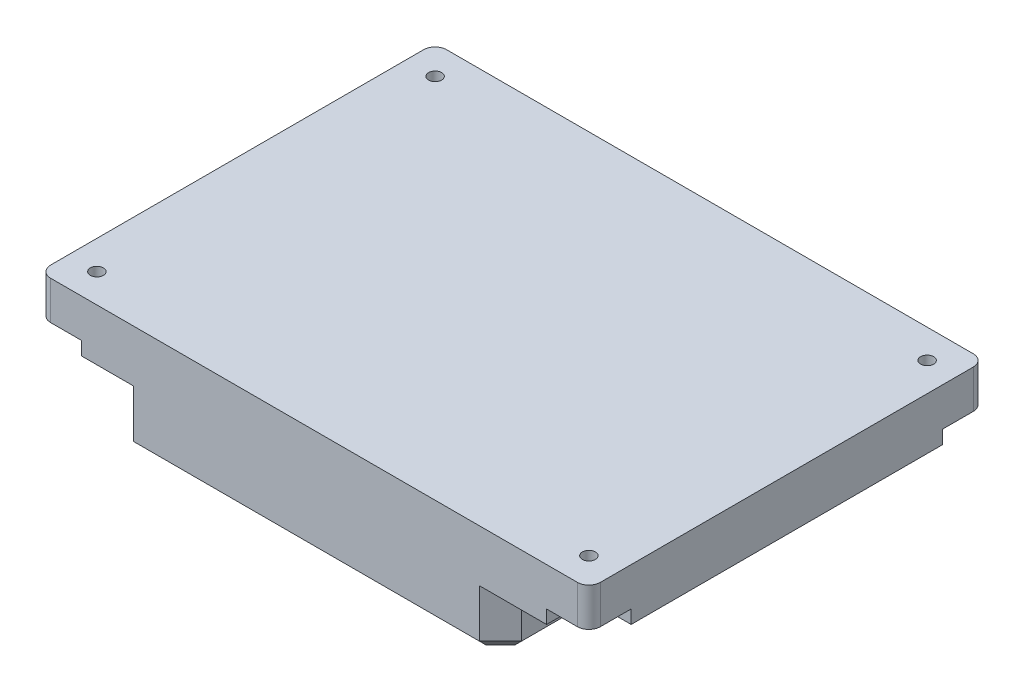
SolidWorks part; units mm, degrees
ref_plane "Front Plane" through (0, 0, 0) normal (0, 0, 1) x (1, 0, 0)
ref_plane "Top Plane" through (0, 0, 0) normal (0, 1, 0) x (1, 0, 0)
ref_plane "Right Plane" through (0, 0, 0) normal (1, 0, 0) x (0, 0, -1)
ref_plane "Plane1" through (0, 3, 0) normal (0, 1, 0) x (1, 0, 0)
sketch "Sketch1" plane through (0, 3, 0) normal (0, 1, 0) x (1, 0, 0)
  line L0 (71.5, -48.5) -> (71.5, 48.5)
  line L1 (68.5, 51.5) -> (-68.5, 51.5)
  line L2 (-71.5, 48.5) -> (-71.5, -48.5)
  line L3 (-68.5, -51.5) -> (68.5, -51.5)
  arc A0 (68.5, -51.5) -> (71.5, -48.5) centre (68.5, -48.5) ccw
  arc A1 (71.5, 48.5) -> (68.5, 51.5) centre (68.5, 48.5) ccw
  arc A2 (-68.5, 51.5) -> (-71.5, 48.5) centre (-68.5, 48.5) ccw
  arc A3 (-71.5, -48.5) -> (-68.5, -51.5) centre (-68.5, -48.5) ccw
  circle A22 centre (-64, 44) radius 1.7
  circle A34 centre (-64, -44) radius 1.7
  circle A40 centre (64, -44) radius 1.7
  circle A55 centre (64, 44) radius 1.7
extrude "Boss-Extrude1" add sketch "Sketch1" against normal blind 13.5
sketch "Sketch2" plane through (0, -10.5, 0) normal (0, -1, 0) x (1, 0, 0)
  line L0 (-71.5, -40.5) -> (-63, -40.5)
  line L1 (-71.5, -48.5) -> (-71.5, 48.5) construction
  line L2 (-60.5, -43) -> (-60.5, -51.5)
  line L3 (68.5, -51.5) -> (-68.5, -51.5) construction
  line L4 (-71.5, -40.5) -> (-71.5, -48.5)
  line L5 (-68.5, -51.5) -> (-60.5, -51.5)
  line L6 (-71.5, 40.5) -> (-63, 40.5)
  line L7 (-60.5, 43) -> (-60.5, 51.5)
  line L8 (-68.5, 51.5) -> (68.5, 51.5) construction
  line L9 (-71.5, 48.5) -> (-71.5, 40.5)
  line L10 (60.5, 51.5) -> (60.5, 43)
  line L11 (-68.5, 51.5) -> (-60.5, 51.5)
  line L12 (60.5, -51.5) -> (60.5, -43)
  line L13 (63, -40.5) -> (71.5, -40.5)
  line L14 (71.5, 48.5) -> (71.5, -48.5) construction
  line L15 (71.5, -40.5) -> (71.5, -48.5)
  line L16 (-63, -40.5) -> (-60.5, -43)
  line L17 (63, 40.5) -> (71.5, 40.5)
  line L18 (60.5, -43) -> (63, -40.5)
  line L19 (60.5, 43) -> (63, 40.5)
  line L20 (-63, 40.5) -> (-60.5, 43)
  line L21 (60.5, 51.5) -> (68.5, 51.5)
  line L22 (71.5, 48.5) -> (71.5, 40.5)
  line L23 (60.5, -51.5) -> (68.5, -51.5)
  arc A1 (-71.5, -48.5) -> (-68.5, -51.5) centre (-68.5, -48.5) ccw construction
  arc A3 (-68.5, 51.5) -> (-71.5, 48.5) centre (-68.5, 48.5) ccw construction
  arc A8 (71.5, 48.5) -> (68.5, 51.5) centre (68.5, 48.5) ccw construction
  arc A9 (-68.5, 51.5) -> (-71.5, 48.5) centre (-68.5, 48.5) ccw
  arc A10 (68.5, -51.5) -> (71.5, -48.5) centre (68.5, -48.5) ccw construction
  arc A11 (71.5, 48.5) -> (68.5, 51.5) centre (68.5, 48.5) ccw
  arc A12 (-71.5, -48.5) -> (-68.5, -51.5) centre (-68.5, -48.5) ccw
  arc A13 (68.5, -51.5) -> (71.5, -48.5) centre (68.5, -48.5) ccw
  point P1 (-60.5, -40.5)
  point P8 (-60.5, 40.5)
  point P15 (60.5, -40.5)
  point P24 (60.5, 40.5)
  dimension "D1" = 11
  dimension "D2" = 11
extrude "Cut-Extrude2" cut sketch "Sketch2" against normal blind 3.5
sketch "Sketch3" plane through (0, -10.5, 0) normal (0, -1, 0) x (1, 0, 0)
  line L0 (-52.5, 46) -> (-52.5, -32)
  line L1 (-60.5, 51.5) -> (60.5, 51.5) construction
  line L2 (-47, -37.5) -> (43, -37.5)
  line L3 (48.5, -32) -> (48.5, 46)
  line L4 (43, 51.5) -> (-47, 51.5)
  line L5 (60.5, -51.5) -> (-60.5, -51.5) construction
  line L6 (-71.5, -40.5) -> (-71.5, 40.5) construction
  line L7 (71.5, 40.5) -> (71.5, -40.5) construction
  line L8 (-52.5, -32) -> (-47, -37.5)
  line L9 (-47, 51.5) -> (-52.5, 46)
  line L10 (48.5, 46) -> (43, 51.5)
  line L11 (43, -37.5) -> (48.5, -32)
  point P0 (-52.5, 51.5)
  point P1 (-52.5, -37.5)
  point P5 (48.5, -37.5)
  point P6 (48.5, 51.5)
  dimension "D1" = 14
  dimension "D2" = 19
  dimension "D3" = 23
extrude "Boss-Extrude2" add sketch "Sketch3" along normal blind 15.5
chamfer "Chamfer1" distance 3 angle 45 8 edges at (-2, -26, -37.5) (-49.75, -26, -34.75) (48.5, -26, 7) (45.75, -26, -34.75) (45.75, -26, 48.75) (-2, -26, 51.5) (-49.75, -26, 48.75) (-52.5, -26, 7)
sketch "Sketch4" plane through (0, -26, 0) normal (0, -1, 0) x (1, 0, 0)
  line L0 (-34.309, 29.3492) -> (33.0383, 29.3492) construction
  line L1 (-16.9136, 16.729) -> (13.6137, 16.729) construction
  text T0 "Expansion" font "Century Gothic" height 10
  text T1 "Hub" font "Century Gothic" height 10
